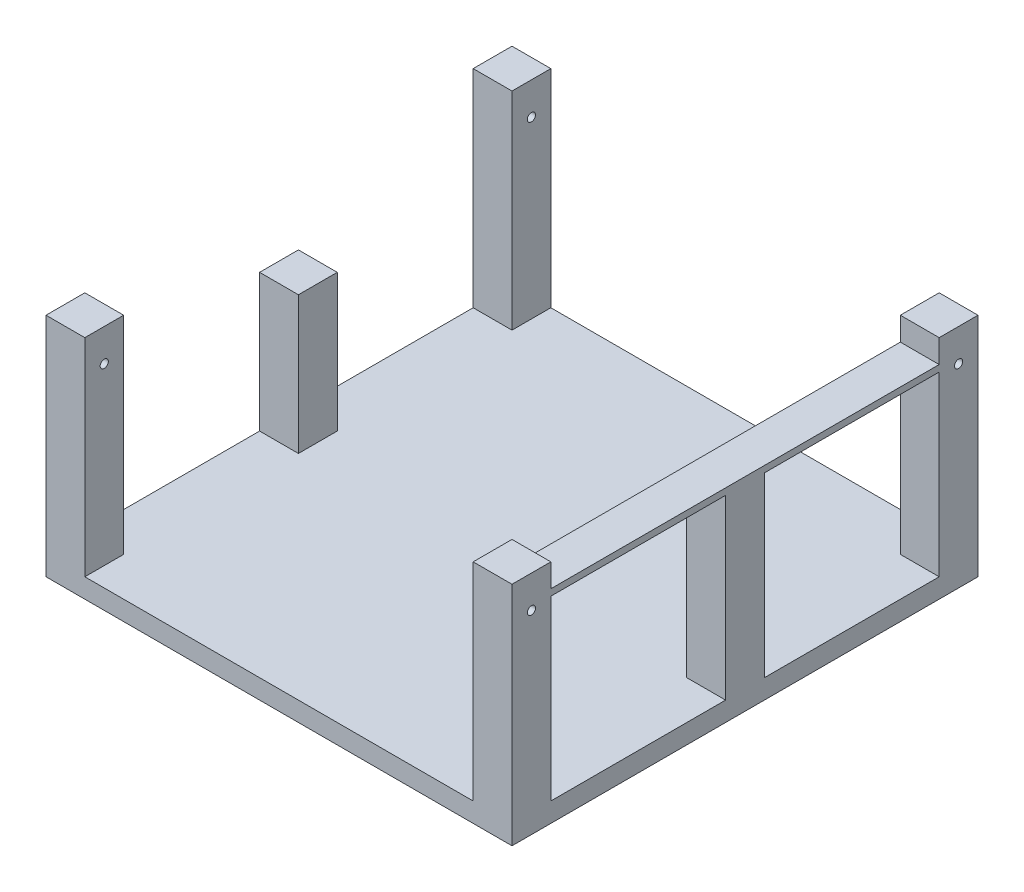
SolidWorks part; units mm, degrees
material "Pine"
ref_plane "Front Plane" through (0, 0, 0) normal (0, 0, 1) x (1, 0, 0)
ref_plane "Top Plane" through (0, 0, 0) normal (0, 1, 0) x (1, 0, 0)
ref_plane "Right Plane" through (0, 0, 0) normal (1, 0, 0) x (0, 0, -1)
sketch "Sketch2" plane through (0, 0, 0) normal (0, 1, 0) x (1, 0, 0)
  line L1 (-228.6, -228.6) -> (228.6, -228.6)
  line L2 (-228.6, -228.6) -> (-228.6, 228.6)
  line L3 (-228.6, 228.6) -> (228.6, 228.6)
  line L4 (228.6, -228.6) -> (228.6, 228.6)
  line L5 (-228.6, -228.6) -> (228.6, 228.6) construction
  line L6 (-228.6, 228.6) -> (228.6, -228.6) construction
  point P0 (0, 0)
  dimension "D1" = 457.2
  dimension "D2" = 457.2
extrude "Boss-Extrude1" add sketch "Sketch2" along normal blind 19.05
sketch "Sketch3" plane through (0, 19.05, 0) normal (0, 1, 0) x (1, 0, 0)
  line L0 (0, 228.6) -> (0, 0) construction
  line L1 (228.6, 228.6) -> (-228.6, 228.6) construction
  line L2 (0, 0) -> (-228.6, 0) construction
  line L3 (-228.6, 228.6) -> (-228.6, -228.6) construction
  line L4 (228.6, 228.6) -> (-228.6, -228.6) construction
  line L5 (190.5, 228.6) -> (190.5, 190.5)
  line L6 (-228.6, 228.6) -> (-190.5, 228.6)
  line L7 (-228.6, 228.6) -> (-228.6, 190.5)
  line L8 (-228.6, 190.5) -> (-190.5, 190.5)
  line L9 (-190.5, 228.6) -> (-190.5, 190.5)
  line L10 (228.6, 190.5) -> (190.5, 190.5)
  line L11 (228.6, 228.6) -> (228.6, 190.5)
  line L12 (228.6, 228.6) -> (190.5, 228.6)
  line L13 (-190.5, -228.6) -> (-190.5, -190.5)
  line L14 (-228.6, -190.5) -> (-190.5, -190.5)
  line L15 (-228.6, -228.6) -> (-228.6, -190.5)
  line L16 (-228.6, -228.6) -> (-190.5, -228.6)
  line L17 (228.6, -190.5) -> (190.5, -190.5)
  line L18 (190.5, -228.6) -> (190.5, -190.5)
  line L19 (228.6, -228.6) -> (190.5, -228.6)
  line L20 (228.6, -228.6) -> (228.6, -190.5)
  dimension "D1" = 38.1
  dimension "D2" = 38.1
extrude "Boss-Extrude2" add sketch "Sketch3" along normal blind 203.2
sketch "Sketch4" plane through (-228.6, 0, 0) normal (-1, 0, 0) x (0, 0, 1)
  line L0 (-209.55, 190.5) -> (-209.55, 222.25) construction
  line L2 (-228.6, 222.25) -> (-190.5, 222.25) construction
  line L3 (0, 19.05) -> (0, 292.6965) construction
  line L4 (-190.5, 19.05) -> (190.5, 19.05) construction
  circle A0 centre (-209.55, 190.5) radius 4
  circle A1 centre (209.55, 190.5) radius 4
  dimension "D1" = 8
  dimension "D2" = 31.75
extrude "Cut-Extrude1" cut sketch "Sketch4" against normal blind 457.2
sketch "Sketch6" plane through (0, 19.05, 0) normal (0, 1, 0) x (1, 0, 0)
  line L0 (-228.6, 0) -> (228.6, 0) construction
  line L1 (-228.6, 190.5) -> (-228.6, -190.5) construction
  line L2 (228.6, -190.5) -> (228.6, 190.5) construction
  line L4 (-190.5, -19.05) -> (-228.6, -19.05)
  line L5 (-190.5, -19.05) -> (-190.5, 19.05)
  line L6 (-190.5, 19.05) -> (-228.6, 19.05)
  line L7 (-228.6, -19.05) -> (-228.6, 19.05)
  line L8 (-190.5, -19.05) -> (-228.6, 19.05) construction
  line L9 (-190.5, 19.05) -> (-228.6, -19.05) construction
  point P6 (-209.55, 0)
  dimension "D1" = 38.1
  dimension "D2" = 38.1
extrude "Boss-Extrude3" add sketch "Sketch6" along normal blind 134.874
sketch "Sketch7" plane through (0, 19.05, 0) normal (0, 1, 0) x (1, 0, 0)
  line L0 (0, 0) -> (228.6, 0) construction
  line L1 (228.6, -190.5) -> (228.6, 190.5) construction
  line L3 (190.5, -19.05) -> (228.6, -19.05)
  line L4 (190.5, -19.05) -> (190.5, 19.05)
  line L5 (190.5, 19.05) -> (228.6, 19.05)
  line L6 (228.6, -19.05) -> (228.6, 19.05)
  line L7 (190.5, -19.05) -> (228.6, 19.05) construction
  line L8 (190.5, 19.05) -> (228.6, -19.05) construction
  point P5 (209.55, 0)
  dimension "D1" = 38.1
  dimension "D2" = 38.1
extrude "Boss-Extrude4" add sketch "Sketch7" along normal blind 173.99
sketch "Sketch8" plane through (0, 193.04, 0) normal (0, 1, 0) x (1, 0, 0)
  line L0 (190.5, 19.05) -> (228.6, -19.05) construction
  line L1 (228.6, 19.05) -> (228.6, 190.5) construction
  line L2 (190.5, -190.5) -> (228.6, -190.5)
  line L3 (190.5, -190.5) -> (190.5, 190.5)
  line L4 (190.5, 190.5) -> (228.6, 190.5)
  line L5 (228.6, -190.5) -> (228.6, 190.5)
  line L6 (190.5, -190.5) -> (228.6, 190.5) construction
  line L7 (190.5, 190.5) -> (228.6, -190.5) construction
  point P4 (209.55, 0)
  dimension "D1" = 381
extrude "Boss-Extrude5" add sketch "Sketch8" along normal blind 6.35
